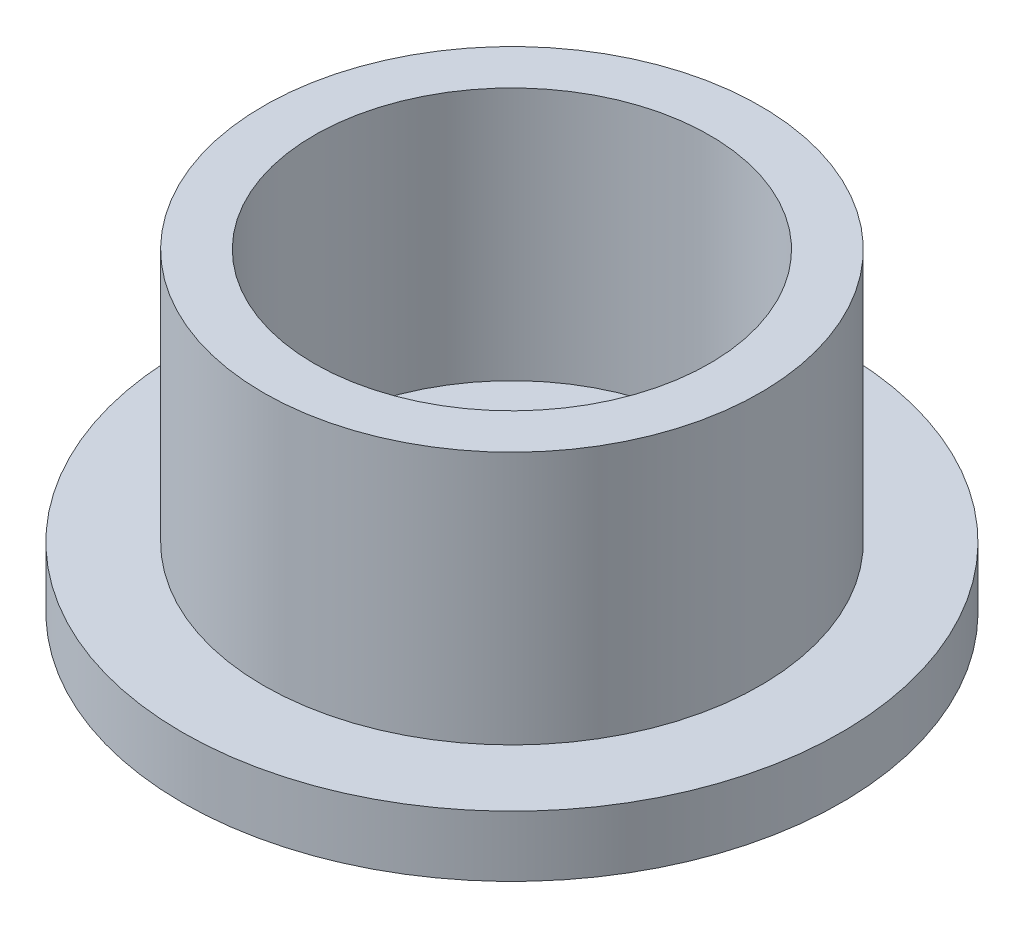
SolidWorks part; units mm, degrees
ref_plane "Front Plane" through (0, 0, 0) normal (0, 0, 1) x (1, 0, 0)
ref_plane "Top Plane" through (0, 0, 0) normal (0, 1, 0) x (1, 0, 0)
ref_plane "Right Plane" through (0, 0, 0) normal (1, 0, 0) x (0, 0, -1)
sketch "Sketch1" plane through (0, 0, 0) normal (0, 1, 0) x (1, 0, 0)
  circle A0 centre (0, 0) radius 6.5
extrude "Boss-Extrude1" add sketch "Sketch1" along normal blind 1.2
sketch "Sketch2" plane through (0, 1.2, 0) normal (0, 1, 0) x (1, 0, 0)
  circle A0 centre (0, 0) radius 4.9
  circle A1 centre (0, 0) radius 3.9
extrude "Boss-Extrude2" add sketch "Sketch2" along normal blind 5
